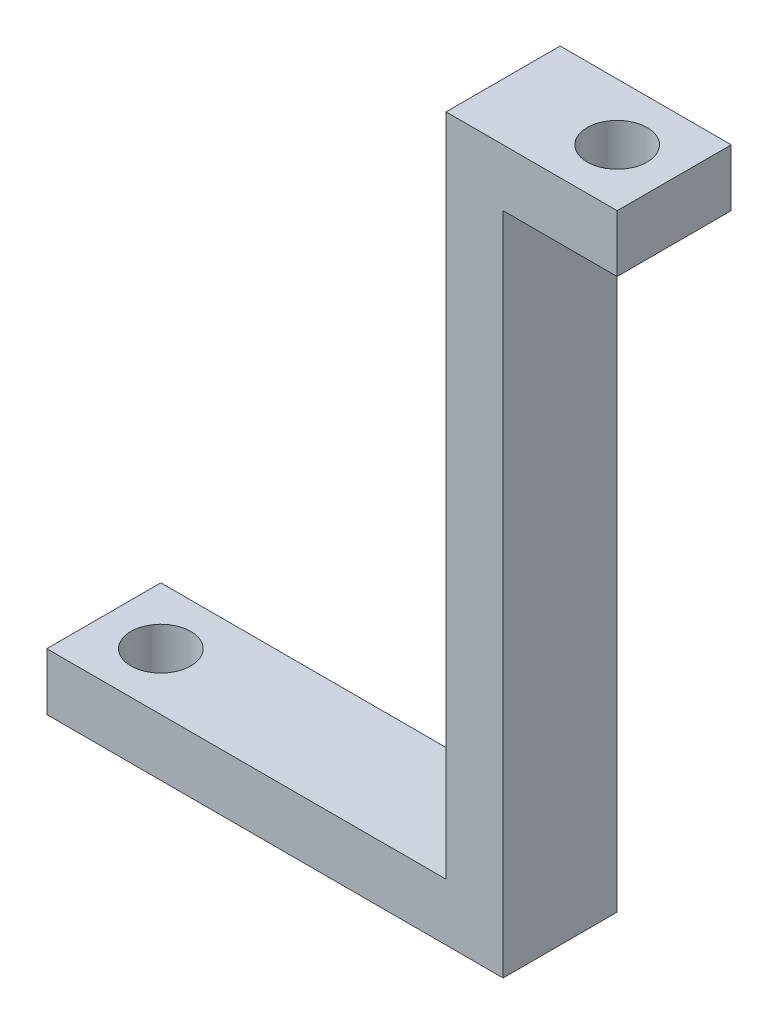
SolidWorks part; units mm, degrees
ref_plane "Front Plane" through (0, 0, 0) normal (0, 0, 1) x (1, 0, 0)
ref_plane "Top Plane" through (0, 0, 0) normal (0, 1, 0) x (1, 0, 0)
ref_plane "Right Plane" through (0, 0, 0) normal (1, 0, 0) x (0, 0, -1)
sketch "Sketch1" plane through (0, 0, 0) normal (0, 1, 0) x (1, 0, 0)
  line L0 (0, 0) -> (-2, 0) construction
  line L1 (-2, 2) -> (12, 2)
  line L2 (-2, 2) -> (-2, -2)
  line L3 (-2, -2) -> (12, -2)
  line L4 (12, 2) -> (12, -2)
  line L5 (0, 0) -> (0, -2) construction
  circle A0 centre (0, 0) radius 1.05
  point P0 (0, 0)
  dimension "D3" = 2.1
  dimension "D1" = 12
  dimension "D2" = 4
  dimension "D4" = 2
extrude "Boss-Extrude1" add sketch "Sketch1" along normal blind 2
sketch "Sketch2" plane through (0, 0, 0) normal (0, 1, 0) x (1, 0, 0)
  line L0 (12, -2) -> (14, -2)
  line L2 (14, -2) -> (14, 2)
  line L3 (14, 2) -> (12, 2)
  line L4 (12, -2) -> (12, 2) construction
  line L5 (12, 2) -> (12, -2)
  dimension "D1" = 2
extrude "Boss-Extrude2" add sketch "Sketch2" along normal up to surface (25.3 mm away)
sketch "Sketch3" plane through (0, 25.3, 0) normal (0, 1, 0) x (1, 0, 0)
  line L8 (14, 2) -> (18, 2)
  line L9 (18, 2) -> (18, -2)
  line L10 (18, -2) -> (14, -2)
  line L11 (14, 2) -> (14, -2)
  line L13 (16, 0) -> (18, 0) construction
  line L14 (16, 0) -> (16, 2) construction
  circle A2 centre (16, 0) radius 1.05
  dimension "D2" = 2.1
  dimension "D1" = 4
extrude "Boss-Extrude3" add sketch "Sketch3" against normal blind 2
